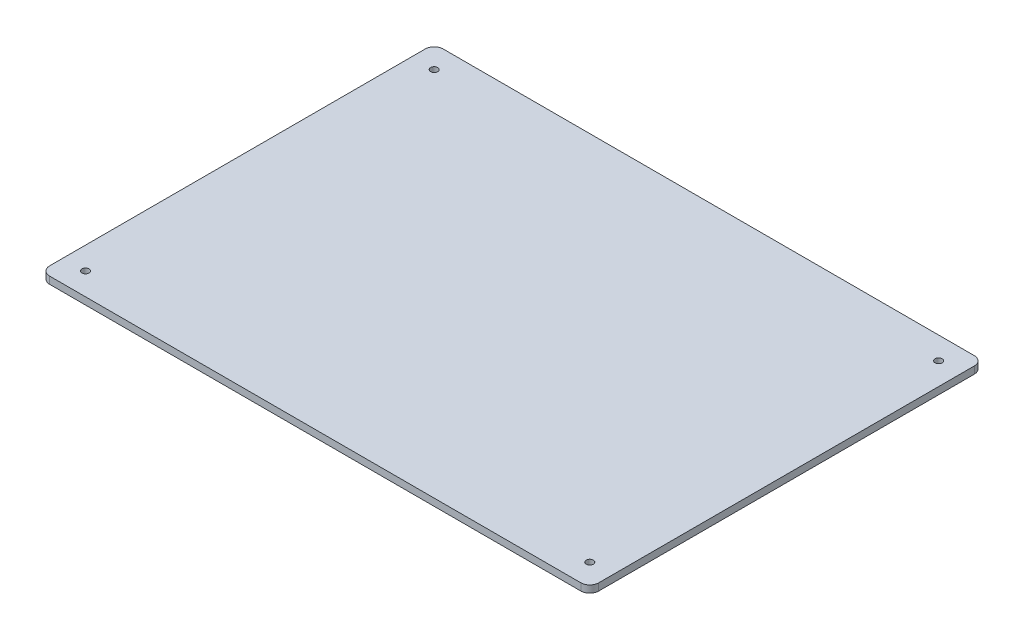
SolidWorks part; units mm, degrees
material "ABS PC"
ref_plane "Front Plane" through (0, 0, 0) normal (0, 0, 1) x (1, 0, 0)
ref_plane "Top Plane" through (0, 0, 0) normal (0, 1, 0) x (1, 0, 0)
ref_plane "Right Plane" through (0, 0, 0) normal (1, 0, 0) x (0, 0, -1)
sketch "Sketch1" plane through (0, 0, 0) normal (0, 1, 0) x (1, 0, 0)
  line L0 (-148.5, 0) -> (148.5, 0) construction
  line L1 (148.5, -105) -> (-148.5, -105) construction
  line L2 (148.5, -105) -> (148.5, 105) construction
  line L3 (148.5, 105) -> (-148.5, 105) construction
  line L4 (-148.5, -105) -> (-148.5, 105) construction
  line L5 (148.5, -105) -> (-148.5, 105) construction
  line L6 (148.5, 105) -> (-148.5, -105) construction
  line L7 (0, 105) -> (0, -105) construction
  point P0 (0, 0)
  point P6 (-141, 97.5)
  point P11 (141, 97.5)
  point P12 (-141, -97.5)
  point P13 (0, 0)
  point P14 (141, -97.5)
  dimension "D1" = 297
  dimension "D2" = 210
  dimension "D3" = 7.5
  dimension "D4" = 7.5
sketch "Sketch2" plane through (0, 0, 0) normal (0, 1, 0) x (1, 0, 0)
  line L0 (-148.5, -105) -> (-148.5, 105) construction
  line L1 (148.5, -110) -> (-148.5, -110)
  line L2 (153.5, -105) -> (153.5, 105)
  line L3 (148.5, 110) -> (-148.5, 110)
  line L4 (-153.5, -105) -> (-153.5, 105)
  line L5 (153.5, -110) -> (-153.5, 110) construction
  line L6 (153.5, 110) -> (-153.5, -110) construction
  line L7 (148.5, 105) -> (-148.5, 105) construction
  arc A0 (153.5, 105) -> (148.5, 110) centre (148.5, 105) ccw
  arc A1 (148.5, -110) -> (153.5, -105) centre (148.5, -105) ccw
  arc A2 (-148.5, -110) -> (-153.5, -105) centre (-148.5, -105) cw
  arc A3 (-148.5, 110) -> (-153.5, 105) centre (-148.5, 105) ccw
  point P0 (0, 0)
  dimension "D3" = 5
  dimension "D1" = 5
  dimension "D2" = 5
extrude "Boss-Extrude1" add sketch "Sketch2" along normal blind 4
hole_wizard "Ø4.0mm Dowel Hole1" positions "Sketch3" profile "Sketch4" hole size "Ø4.0" standard "ANSI Metric" end condition through all
sketch "Sketch3" plane through (0, 4, 0) normal (0, 1, 0) x (1, 0, 0)
  point P0 (-141, 97.5)
  point P3 (-141, -97.5)
  point P6 (141, -97.5)
  point P9 (141, 97.5)
sketch "Sketch4" plane through (-141, 4, -97.5) normal (1, 0, 0) x (0, 0, 1)
  line L0 (0, 0) -> (0, 4)
  line L1 (0, 4) -> (2, 4)
  line L2 (2, 4) -> (2, 0)
  line L5 (2, 0) -> (0, 0)
  line L11 (0, -6.35) -> (0, 107.95) construction
  dimension "Thru Hole Dia." = 4
  dimension "Thru Hole Depth" = 4
